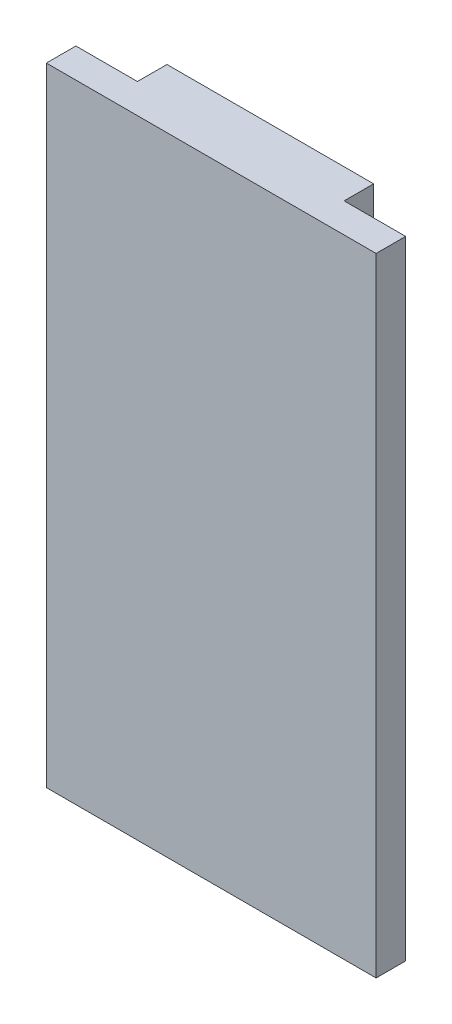
SolidWorks part; units mm, degrees
material "Polyurethane Foam Rigid"
ref_plane "Front Plane" through (0, 0, 0) normal (0, 0, 1) x (1, 0, 0)
ref_plane "Top Plane" through (0, 0, 0) normal (0, 1, 0) x (1, 0, 0)
ref_plane "Right Plane" through (0, 0, 0) normal (1, 0, 0) x (0, 0, -1)
sketch "Sketch1" plane through (0, 0, 0) normal (0, 0, 1) x (1, 0, 0)
  line L1 (-266.7, -809.625) -> (266.7, -809.625)
  line L2 (-266.7, -809.625) -> (-266.7, 809.625)
  line L3 (-266.7, 809.625) -> (266.7, 809.625)
  line L4 (266.7, -809.625) -> (266.7, 809.625)
  line L5 (-266.7, -809.625) -> (266.7, 809.625) construction
  line L6 (-266.7, 809.625) -> (266.7, -809.625) construction
  point P0 (0, 0)
extrude "Boss-Extrude1" add sketch "Sketch1" along normal blind 76.2
sketch "Sketch2" plane through (0, 0, 76.2) normal (0, 0, 1) x (1, 0, 0)
  line L1 (-425.45, 809.625) -> (425.45, 809.625)
  line L2 (-425.45, 809.625) -> (-425.45, -809.625)
  line L3 (-425.45, -809.625) -> (425.45, -809.625)
  line L4 (425.45, 809.625) -> (425.45, -809.625)
  line L5 (-425.45, 809.625) -> (425.45, -809.625) construction
  line L6 (-425.45, -809.625) -> (425.45, 809.625) construction
  point P0 (0, 0)
extrude "Boss-Extrude2" add sketch "Sketch2" along normal blind 76.2
